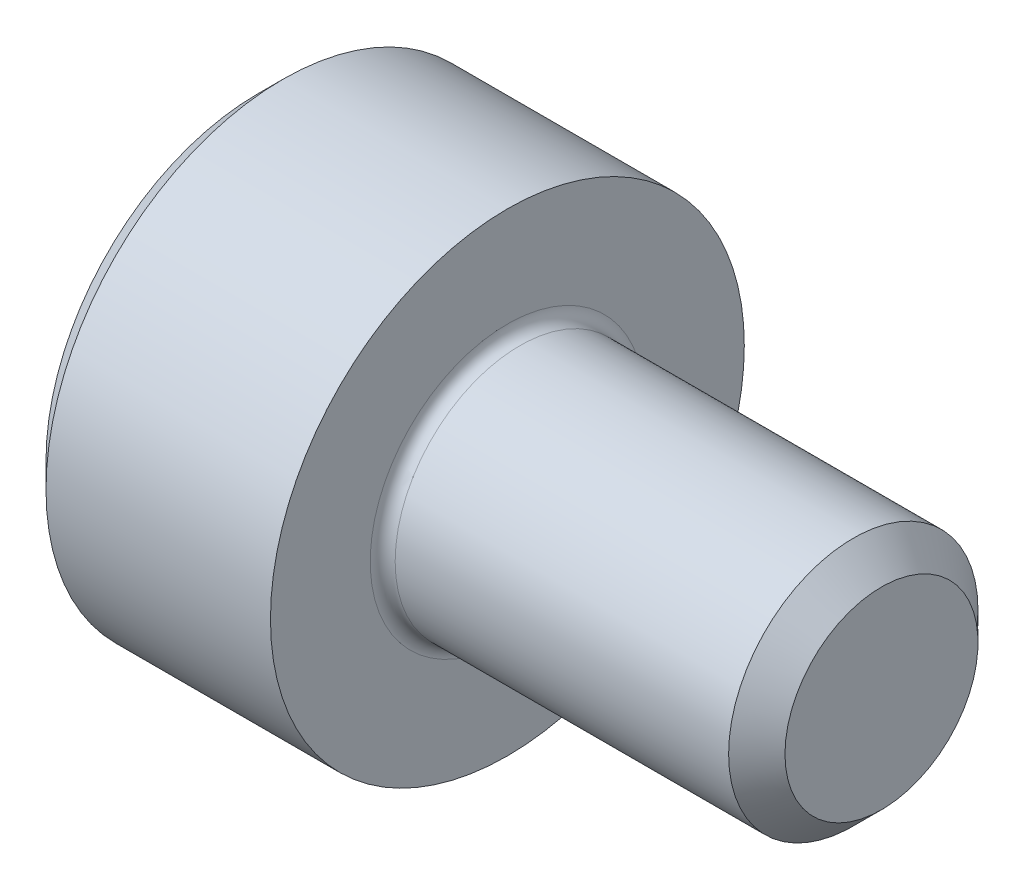
SolidWorks part; units mm, degrees
ref_plane "Plane1" through (0, 0, 0) normal (0, 0, 1) x (1, 0, 0)
ref_plane "Plane2" through (0, 0, 0) normal (0, 1, 0) x (1, 0, 0)
ref_plane "Plane3" through (0, 0, 0) normal (1, 0, 0) x (0, 0, -1)
sketch "BodySke" plane through (0, 0, 0) normal (0, 0, 1) x (1, 0, 0)
  line L0 (0, 0) -> (0, 1.7)
  line L1 (0.2, 1.9) -> (2, 1.9)
  line L2 (2, 1.9) -> (2, 1)
  line L3 (2, 1) -> (4.774, 1)
  line L4 (5, 0.774) -> (5, 0)
  line L5 (5, 0) -> (0, 0)
  line L6 (-31.75, 0) -> (127, 0) construction
  line L7 (0, 1.7) -> (0.2, 1.9)
  line L8 (5, 0.774) -> (4.774, 1)
  line L9 (0, -1.7) -> (0.2, -1.9) construction
  line L10 (5, -0.774) -> (4.774, -1) construction
  line L11 (2.4, 9.525) -> (2.4, 3.175) construction
  line L12 (2, 9.525) -> (2, 3.175) construction
  line L13 (-45, 9.525) -> (-45, 3.175) construction
  dimension "Diameter" = 2
  dimension "Head_ht" = 2
  dimension "Length" = 3
  dimension "Body_ch_ang" = 45
  dimension "Head_dia" = 3.8
  dimension "Head_ch_ang" = 45
  dimension "Minor_dia" = 1.548
  dimension "Advance" = 0.4
  dimension "Thread_nom" = 3
  dimension "Thread_length" = 50
  dimension "Head_ch_ht" = 0.2
revolve "Base-Revolve" add sketch "BodySke"
cosmetic thread "ThreadCosmetic" [suppressed]
fillet "Fillet1" radius 0.1 1 edges at (2, 0, 1)
sketch "Sketch2" plane through (0, 0, 0) normal (0, 0, 1) x (1, 0, 0)
  line L0 (0, 0.7725) -> (1, 0.7725)
  line L1 (1, 0.7725) -> (1.446, 0)
  line L2 (-31.75, 0) -> (127, 0) construction
  line L3 (1.446, 0) -> (0, 0)
  line L4 (0, 0) -> (0, 0.7725)
  line L5 (0, 1.7) -> (0, -1.7) construction
  line L6 (0, 0) -> (47.625, 0) construction
  line L7 (2, -1.9) -> (2, 1.9) construction
  dimension "D1" = 0.7725
  dimension "D2" = 60
  dimension "Wall_thickness" = 1
revolve "Hex-PreBroach" cut sketch "Sketch2" angle 360 about L6
sketch "Sketch3" plane through (0, 0, 0) normal (-1, 0, 0) x (0, 0.5, 0.866)
  line L0 (0.446, 0.7725) -> (-0.446, 0.7725)
  line L1 (-0.446, 0.7725) -> (-0.892, 0)
  line L2 (0.446, 0.7725) -> (0.892, 0)
  line L3 (0.446, -0.7725) -> (0.892, 0)
  line L4 (0.446, -0.7725) -> (-0.446, -0.7725)
  line L5 (-0.446, -0.7725) -> (-0.892, 0)
  dimension "D1" = 0.7725
  dimension "D2" = 0.7725
  dimension "Hex_size" = 1.545
extrude "Hex" cut sketch "Sketch3" against normal blind 1
sketch "Sketch4" plane through (0, 0, 0) normal (-1, 0, 0) x (0, 0, 1)
  line L0 (0, 0) -> (0.9398, 0)
  line L1 (0, 0) -> (6.1484, 3.5498) construction
  line L2 (0, 0) -> (0.4699, 0.8139)
  line L3 (0.7832, 0.2175) -> (0.8962, 0.2828)
  line L4 (0.58, 0.5695) -> (0.693, 0.6348)
  arc A0 (0.7832, 0.2175) -> (0.58, 0.5695) centre (0, 0) ccw
  arc A1 (0.9398, 0) -> (0.8962, 0.2828) centre (0, 0) ccw
  arc A2 (0.4699, 0.8139) -> (0.693, 0.6348) centre (0, 0) cw
  dimension "D1" = 30
  dimension "Spline_n_dim" = 1.6256
  dimension "Spline_m_dim" = 1.8796
  dimension "D2" = 60
  dimension "D3" = 0.2032
  dimension "Spline_p_dim" = 0.4064
extrude "Spline" [suppressed] cut sketch "Sketch4" against normal blind 1
pattern_circular "CirPattern1" [suppressed] count 6 every 60
sketch "Sketch5" plane through (0, 0, 0) normal (0, 0, 1) x (1, 0, 0)
  line L0 (-31.75, 0) -> (127, 0) construction
  line L2 (0, 1.7) -> (0, -1.7) construction
  circle A0 centre (0.1, 0) radius 0.005
  dimension "Drilled_hole_dia" = 0.01
  dimension "Drilled_hole_loc" = 0.1
extrude "Hole" [suppressed] cut sketch "Sketch5" against normal through all and the other way through all
pattern_circular "Drilled-4" [suppressed] count 2 every 60
pattern_circular "Drilled-6" [suppressed] count 3 every 60
sketch "ThdSchSke" plane through (0, 0, 0) normal (0, 0, 1) x (1, 0, 0)
  line L0 (2.4, -0.774) -> (2.2418, -1)
  line L1 (2.4, -0.774) -> (2.5582, -1)
  line L2 (2.5582, -1) -> (2.5582, -1.25)
  line L3 (-3.175, 0) -> (5.1513, 0) construction
  line L5 (2.5582, -1.25) -> (2.2418, -1.25)
  line L6 (2.2418, -1.25) -> (2.2418, -1)
  line L7 (0, 1.7) -> (0, -1.7) construction
  dimension "Thread_minor" = 1.548
  dimension "Diameter" = 2
  dimension "Start" = 2.4
  dimension "SideAngle" = 55
  dimension "VeeAngle" = 70
  dimension "Overcut" = 2.5
revolve "ThreadSchematic" [suppressed] cut sketch "ThdSchSke" angle 360 about L3
pattern_linear "ThdSchPat" [suppressed]
equation "\"D2@Sketch3\" = \"Hex_size@Sketch3\" / 2"
equation "\"D1@Sketch3\" = \"Hex_size@Sketch3\" / 2"
equation "\"D1@Sketch2\" = \"Hex_size@Sketch3\" / 2"
equation "\"D3@Sketch4\" = \"Spline_p_dim@Sketch4\" / 2"
equation "\"Thread_minor@ThreadCosmetic\"  =  \"Minor_dia@BodySke\""
equation "\"D2@CirPattern1\" = 360 / \"Num_teeth@CirPattern1\""
equation "\"Wall_thickness@Sketch2\" = \"Head_ht@BodySke\" - \"Key_eng@Hex\""
equation "\"Thread_length@ThreadCosmetic\" = ((sgn( (\"Length@BodySke\" - \"Advance@BodySke\" ) - \"Thread_nom@BodySke\" )-1)*( (\"Length@BodySke\" - \"Advance@BodySke\" ) - \"Thread_nom@BodySke\" ))/-2+ \"Thread_nom@BodySke\""
equation "\"Thread_minor@ThdSchSke\" = \"Minor_dia@BodySke\""
equation "\"Diameter@ThdSchSke\" = \"Diameter@BodySke\""
equation "\"Overcut@ThdSchSke\" = \"Diameter@BodySke\" * 1.25"
equation "\"Start@ThdSchSke\" = \"Head_ht@BodySke\" + \"Length@BodySke\" - \"Thread_length@ThreadCosmetic\"  '---Non-countersunk---"
equation "\"Num_threads@ThdSchPat\" = int( \"Thread_length@ThreadCosmetic\" / \"Advance@BodySke\" + 0.999 )  + 1"
equation "\"Advance@ThdSchPat\" = \"Thread_length@ThreadCosmetic\" /  (\"Num_threads@ThdSchPat\" - 1) 'relax it"
equation "\"Num_threads@ThdSchPat\" = \"Num_threads@ThdSchPat\" - sgn( \"Num_threads@ThdSchPat\" - 1) '---chamfered tips only---"
